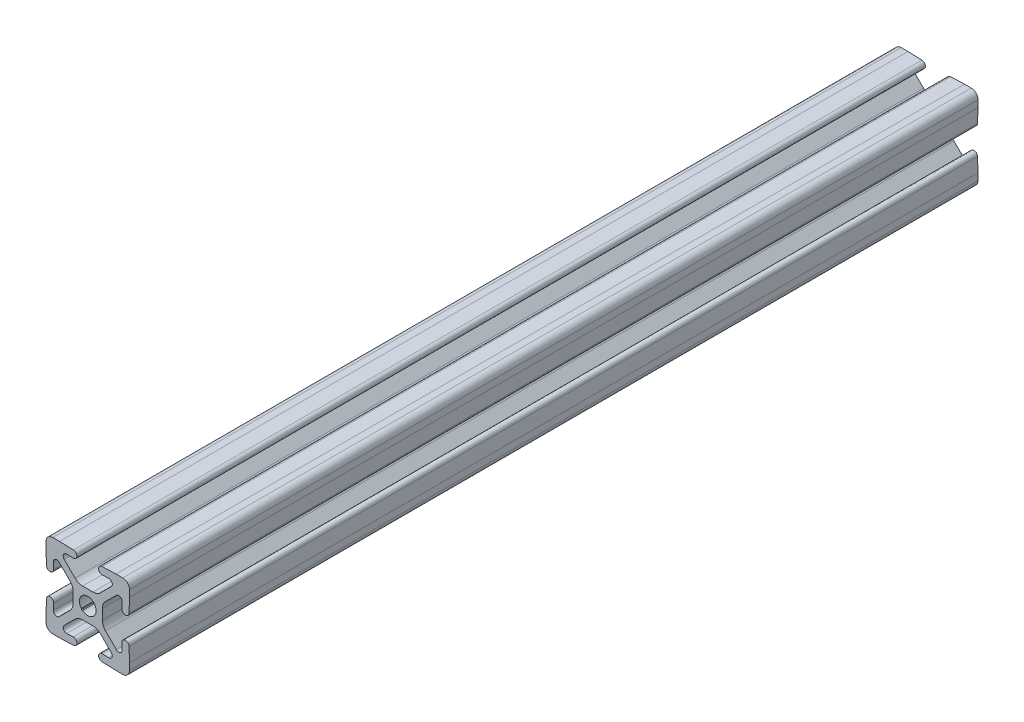
SolidWorks part; units mm, degrees
ref_plane "Front Plane" through (0, 0, 0) normal (0, 0, 1) x (1, 0, 0)
ref_plane "Top Plane" through (0, 0, 0) normal (0, 1, 0) x (1, 0, 0)
ref_plane "Right Plane" through (0, 0, 0) normal (1, 0, 0) x (0, 0, -1)
sketch "Model" plane through (0, 0, 0) normal (0, 0, 1) x (1, 0, 0)
  line L38 (50.6495, 75.4336) -> (50.2699, 75.4336)
  line L39 (50.2699, 75.4336) -> (50.2699, 75.8133)
  line L40 (50.66, 72.9999) -> (53.7746, 72.9999)
  line L41 (56.0196, 72.0699) -> (59.2642, 68.8254)
  line L42 (58.5103, 67.0916) -> (56.5725, 67.1592)
  line L43 (56.498, 65.0269) -> (60.6773, 64.881)
  line L44 (60.6773, 64.881) -> (62.7107, 64.881)
  line L45 (64.7173, 66.8876) -> (64.7173, 68.921)
  line L46 (64.7173, 68.921) -> (64.5713, 73.1002)
  line L47 (62.439, 73.0257) -> (62.5067, 71.0879)
  line L48 (60.7729, 70.334) -> (57.5283, 73.5786)
  line L49 (56.5984, 75.8237) -> (56.5984, 78.9383)
  line L50 (57.5283, 81.1833) -> (60.7729, 84.4279)
  line L51 (62.5067, 83.674) -> (62.439, 81.7362)
  line L52 (64.5713, 81.6617) -> (64.7173, 85.841)
  line L53 (64.7173, 85.841) -> (64.7173, 87.8744)
  line L54 (62.7107, 89.881) -> (60.6773, 89.881)
  line L55 (60.6773, 89.881) -> (56.498, 89.735)
  line L56 (56.5725, 87.6027) -> (58.5103, 87.6704)
  line L57 (59.2642, 85.9366) -> (56.0196, 82.692)
  line L58 (53.7746, 81.7621) -> (50.66, 81.7621)
  line L59 (48.4149, 82.692) -> (45.1703, 85.9366)
  line L60 (45.9242, 87.6704) -> (47.862, 87.6027)
  line L61 (47.9365, 89.735) -> (43.7573, 89.881)
  line L62 (43.7573, 89.881) -> (41.7239, 89.881)
  line L63 (39.7173, 87.8744) -> (39.7173, 85.841)
  line L64 (39.7173, 85.841) -> (39.8632, 81.6617)
  line L65 (41.9955, 81.7362) -> (41.9278, 83.674)
  line L66 (43.6616, 84.4279) -> (46.9062, 81.1833)
  line L67 (47.8361, 78.9383) -> (47.8361, 75.8237)
  line L68 (46.9062, 73.5786) -> (43.6616, 70.334)
  line L69 (41.9278, 71.0879) -> (41.9955, 73.0257)
  line L70 (39.8632, 73.1002) -> (39.7173, 68.921)
  line L71 (39.7173, 68.921) -> (39.7173, 66.8876)
  line L72 (41.7239, 64.881) -> (43.7573, 64.881)
  line L73 (43.7573, 64.881) -> (47.9365, 65.0269)
  line L74 (47.862, 67.1592) -> (45.9242, 67.0916)
  line L75 (45.1703, 68.8254) -> (48.4149, 72.0699)
  arc A29 (50.6495, 75.4336) -> (50.2699, 75.8133) centre (52.2173, 77.381) ccw
  arc A30 (56.0196, 72.0699) -> (53.7746, 72.9999) centre (53.7746, 69.8249) ccw
  arc A31 (58.5103, 67.0916) -> (59.2642, 68.8254) centre (58.5458, 68.1069) ccw
  arc A32 (56.5725, 67.1592) -> (56.498, 65.0269) centre (56.5353, 66.0931) ccw
  arc A33 (62.7107, 64.881) -> (64.7173, 66.8876) centre (62.7107, 66.8876) ccw
  arc A34 (64.5713, 73.1002) -> (62.439, 73.0257) centre (63.5052, 73.063) ccw
  arc A35 (60.7729, 70.334) -> (62.5067, 71.0879) centre (61.4913, 71.0525) ccw
  arc A36 (56.5984, 75.8237) -> (57.5283, 73.5786) centre (59.7734, 75.8237) ccw
  arc A37 (57.5283, 81.1833) -> (56.5984, 78.9383) centre (59.7734, 78.9383) ccw
  arc A38 (62.5067, 83.674) -> (60.7729, 84.4279) centre (61.4913, 83.7095) ccw
  arc A39 (62.439, 81.7362) -> (64.5713, 81.6617) centre (63.5052, 81.699) ccw
  arc A40 (64.7173, 87.8744) -> (62.7107, 89.881) centre (62.7107, 87.8744) ccw
  arc A41 (56.498, 89.735) -> (56.5725, 87.6027) centre (56.5353, 88.6689) ccw
  arc A42 (59.2642, 85.9366) -> (58.5103, 87.6704) centre (58.5458, 86.655) ccw
  arc A43 (53.7746, 81.7621) -> (56.0196, 82.692) centre (53.7746, 84.9371) ccw
  arc A44 (48.4149, 82.692) -> (50.66, 81.7621) centre (50.66, 84.9371) ccw
  arc A45 (45.9242, 87.6704) -> (45.1703, 85.9366) centre (45.8887, 86.655) ccw
  arc A46 (47.862, 87.6027) -> (47.9365, 89.735) centre (47.8993, 88.6689) ccw
  arc A47 (41.7239, 89.881) -> (39.7173, 87.8744) centre (41.7239, 87.8744) ccw
  arc A48 (39.8632, 81.6617) -> (41.9955, 81.7362) centre (40.9293, 81.699) ccw
  arc A49 (43.6616, 84.4279) -> (41.9278, 83.674) centre (42.9432, 83.7095) ccw
  arc A50 (47.8361, 78.9383) -> (46.9062, 81.1833) centre (44.6611, 78.9383) ccw
  arc A51 (46.9062, 73.5786) -> (47.8361, 75.8237) centre (44.6611, 75.8237) ccw
  arc A52 (41.9278, 71.0879) -> (43.6616, 70.334) centre (42.9432, 71.0525) ccw
  arc A53 (41.9955, 73.0257) -> (39.8632, 73.1002) centre (40.9293, 73.063) ccw
  arc A54 (39.7173, 66.8876) -> (41.7239, 64.881) centre (41.7239, 66.8876) ccw
  arc A55 (47.9365, 65.0269) -> (47.862, 67.1592) centre (47.8993, 66.0931) ccw
  arc A56 (45.1703, 68.8254) -> (45.9242, 67.0916) centre (45.8887, 68.1069) ccw
  arc A57 (50.66, 72.9999) -> (48.4149, 72.0699) centre (50.66, 69.8249) ccw
extrude "Boss-Extrude1" add sketch "Model" along normal blind 254
